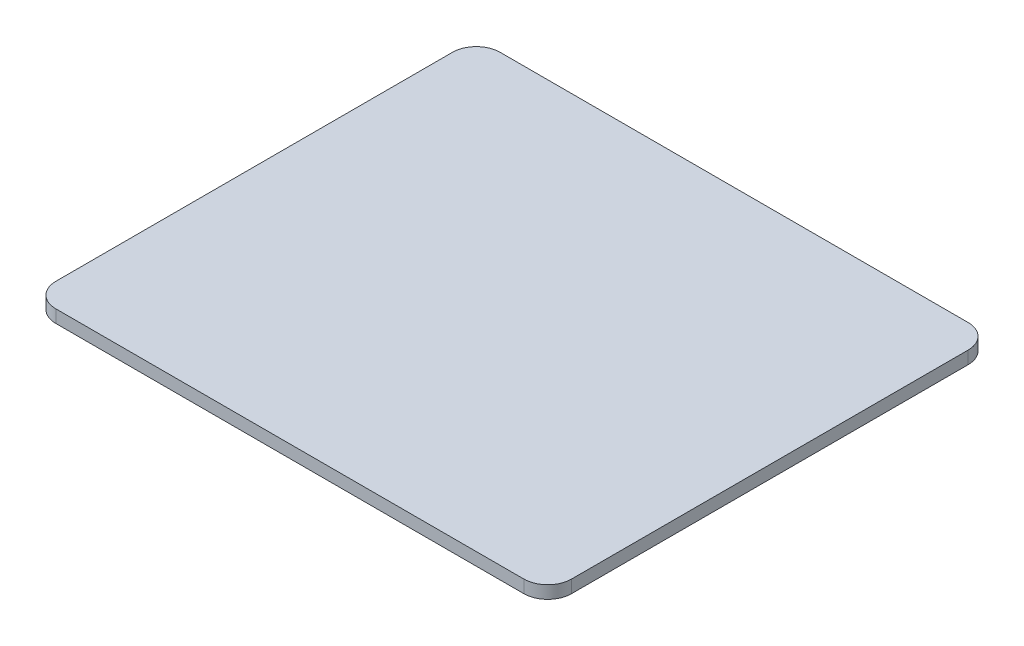
SolidWorks part; units mm, degrees
ref_plane "Front Plane" through (0, 0, 0) normal (0, 0, 1) x (1, 0, 0)
ref_plane "Top Plane" through (0, 0, 0) normal (0, 1, 0) x (1, 0, 0)
ref_plane "Right Plane" through (0, 0, 0) normal (1, 0, 0) x (0, 0, -1)
sketch "Sketch2" plane through (0, 0, 0) normal (0, 1, 0) x (1, 0, 0)
  line L1 (32.5, -28) -> (-32.5, -28)
  line L2 (32.5, -28) -> (32.5, 28)
  line L3 (32.5, 28) -> (-32.5, 28)
  line L4 (-32.5, -28) -> (-32.5, 28)
  line L5 (32.5, -28) -> (-32.5, 28) construction
  line L6 (32.5, 28) -> (-32.5, -28) construction
  point P0 (0, 0)
  dimension "D1" = 65
  dimension "D2" = 56
extrude "Boss-Extrude1" add sketch "Sketch2" along normal blind 1.6
fillet "Fillet1" radius 3 4 edges at (-32.5, 0.8, -28) (32.5, 0.8, -28) (32.5, 0.8, 28) (-32.5, 0.8, 28)
